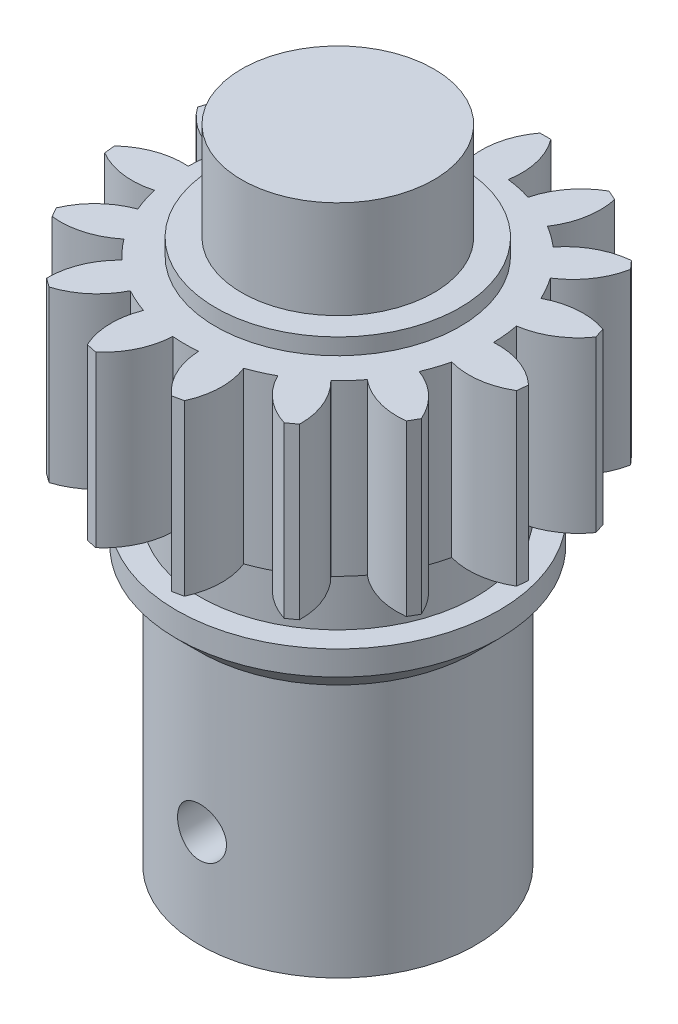
SolidWorks part; units mm, degrees
ref_plane "Plano frontal" through (0, 0, 0) normal (0, 0, 1) x (1, 0, 0)
ref_plane "Plano superior" through (0, 0, 0) normal (0, 1, 0) x (1, 0, 0)
ref_plane "Plano direito" through (0, 0, 0) normal (1, 0, 0) x (0, 0, -1)
sketch "Esboço1" plane through (0, 0, 0) normal (0, 0, 1) x (1, 0, 0)
  line L0 (0, 0) -> (0, 39.4)
  line L1 (0, 0) -> (8.47, 0)
  line L2 (8.47, 0) -> (8.47, 15.58)
  line L3 (8.47, 15.58) -> (9.9, 17.01)
  line L4 (9.9, 17.01) -> (9.9, 18.51)
  line L5 (9.9, 18.51) -> (8.47, 18.51)
  line L6 (8.47, 18.51) -> (8.47, 22)
  line L7 (8.47, 22) -> (9.374, 22)
  line L8 (9.374, 22) -> (9.374, 32.4)
  line L9 (9.374, 32.4) -> (7.5, 32.4)
  line L10 (7.5, 32.4) -> (7.5, 33.4)
  line L11 (7.5, 33.4) -> (5.9, 33.4)
  line L12 (5.9, 33.4) -> (5.9, 39.4)
  line L13 (5.9, 39.4) -> (0, 39.4)
  dimension "D1" = 8.47
  dimension "D2" = 22
  dimension "D3" = 3.49
  dimension "D4" = 1.5
  dimension "D5" = 135
  dimension "D6" = 9.9
  dimension "D7" = 9.374
  dimension "D8" = 7.5
  dimension "D9" = 10.4
  dimension "D10" = 1
  dimension "D11" = 6
  dimension "D12" = 5.9
revolve "Revolução1" add sketch "Esboço1" angle 360 about L0
sketch "Esboço2" plane through (0, 32.4, 0) normal (0, 1, 0) x (1, 0, 0)
  line L0 (-0.337, 12.746) -> (0.337, 12.746)
  line L1 (0, 0) -> (0, 0.674) construction
  line L2 (0, 0) -> (0, 12.746) construction
  line L3 (0, 0) -> (3.269, 10.0539) construction
  arc A1 (1.1676, 9.301) -> (-1.1676, 9.301) centre (0, 0) ccw
  arc A3 (0.337, 12.746) -> (1.1676, 9.301) centre (-3.269, 10.0539) cw
  arc A4 (-0.337, 12.746) -> (-1.1676, 9.301) centre (3.269, 10.0539) ccw
  point P3 (0, 12.746)
  dimension "D2" = 12.746
  dimension "D3" = 18.012
  dimension "D5" = 18.748
  dimension "D1" = 0.674
  dimension "D4" = 10.572
extrude "Ressalto-extrusão1" add sketch "Esboço2" against normal up to surface (10.4 mm away) up to face at (0, 22, -9.374)
pattern_circular "PadrãoCircular1" count 15 over 360 about axis through (0, 0, 0) along (0, 1, 0) of "Ressalto-extrusão1"
sketch "Esboço3" plane through (0, 0, 0) normal (0, -1, 0) x (1, 0, 0)
  line L0 (-3.25, 4.7183) -> (-3.25, -5.2191) construction
  line L1 (2.65, 1.8815) -> (2.65, -1.8815)
  line L2 (3.2, -5.2191) -> (3.2, 4.7183) construction
  line L3 (-2.7, 1.809) -> (-2.7, -1.809)
  arc A0 (2.65, 1.8815) -> (-2.7, 1.809) centre (0, 0) ccw
  arc A2 (-2.7, -1.809) -> (2.65, -1.8815) centre (0, 0) ccw
  point P11 (0, 0)
  point P12 (-2.75, 1.3592)
  point P13 (-2.75, -1.2917)
  point P14 (0, 0)
  point P15 (0, 0)
  point P16 (0, 0)
  dimension "D1" = 6.5
  dimension "D2" = 0.55
  dimension "D3" = 0.55
  dimension "D4" = 3.2
extrude "Corte-extrusão1" cut sketch "Esboço3" against normal blind 22
sketch "Esboço4" plane through (0, 0, 0) normal (0, -1, 0) x (1, 0, 0)
  circle A0 centre (0, 0) radius 3.25
  dimension "D1" = 6.5
extrude "Corte-extrusão2" cut sketch "Esboço4" against normal blind 4
sketch "Esboço7" plane through (0, 0, 0) normal (0, 0, 1) x (1, 0, 0)
  circle A0 centre (0, 6) radius 1.5
  point P2 (0, 0)
  dimension "D2" = 3
  dimension "D1" = 6
extrude "Corte-extrusão4" cut sketch "Esboço7" against normal through all both and the other way through all contours A0
